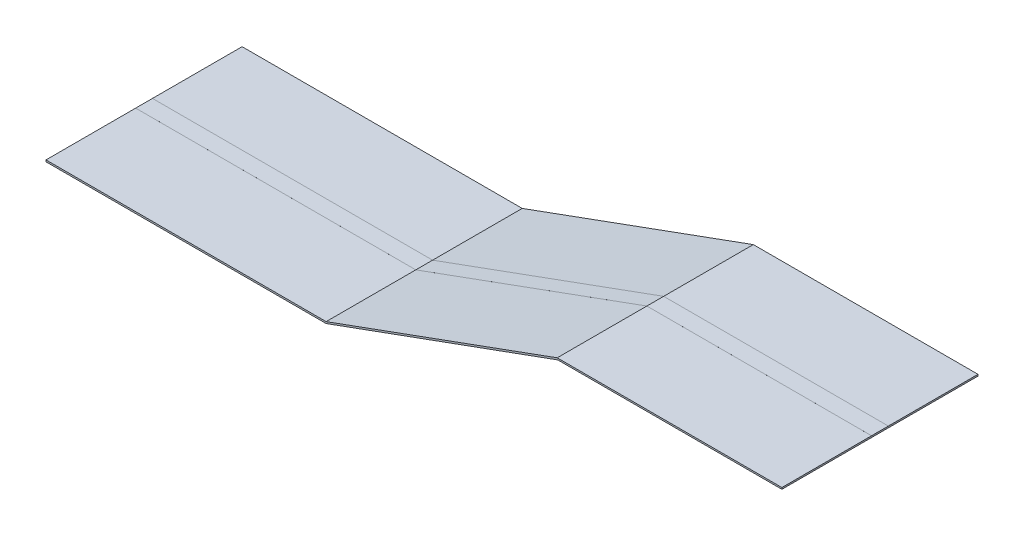
SolidWorks part; units mm, degrees
ref_plane "Front Plane" through (0, 0, 0) normal (0, 0, 1) x (1, 0, 0)
ref_plane "Top Plane" through (0, 0, 0) normal (0, 1, 0) x (1, 0, 0)
ref_plane "Right Plane" through (0, 0, 0) normal (1, 0, 0) x (0, 0, -1)
sketch "Sketch2" plane through (0, 0, 0) normal (0, 0, 1) x (1, 0, 0)
  line L0 (0, 0) -> (-500, 0)
  line L1 (-500, 0) -> (-500, 3)
  line L2 (-500, 3) -> (0, 3)
  line L3 (0, 3) -> (412.4375, 153.3075)
  line L5 (413.4648, 150.4889) -> (0, 0)
  line L6 (413.4648, 150.4889) -> (813.4648, 150.4889)
  line L7 (412.4375, 153.3075) -> (813.4648, 153.3075)
  line L8 (813.4648, 153.3075) -> (813.4648, 150.4889)
  dimension "D1" = 3
  dimension "D2" = 3
  dimension "D3" = 440
  dimension "D4" = 500
  dimension "D5" = 500
  dimension "D6" = 20
  dimension "D7" = 2.8187
  dimension "D8" = 160
  dimension "D9" = 400
  dimension "D10" = 438.9727
extrude "Boss-Extrude3" add sketch "Sketch2" along normal blind 350
sketch "Sketch5" plane through (0, 3, 0) normal (0, 1, 0) x (1, 0, 0)
  line L0 (0, -175) -> (-500, -175) construction
  line L1 (0, -350) -> (0, 0) construction
  line L2 (-500, -350) -> (-500, 0) construction
  line L4 (-500, -190) -> (0, -190)
  line L5 (-500, -190) -> (-500, -160)
  line L6 (-500, -160) -> (0, -160)
  line L7 (0, -190) -> (0, -160)
  line L8 (-500, -190) -> (0, -160) construction
  line L9 (-500, -160) -> (0, -190) construction
  point P6 (-250, -175)
  dimension "D1" = 15
extrude "Boss-Extrude4" add sketch "Sketch5" along normal blind 0.01
sketch "Sketch6" plane through (-0.9651, 2.6483, 0) normal (-0.3424, 0.9396, 0) x (0.9396, 0.3424, 0)
  line L0 (440, -175) -> (1.0272, -175) construction
  line L1 (440, -350) -> (440, 0) construction
  line L2 (1.0272, -190) -> (1.0272, -160) construction
  line L4 (440, -190) -> (1.0272, -190)
  line L5 (440, -190) -> (440, -160)
  line L6 (440, -160) -> (1.0272, -160)
  line L7 (1.0272, -190) -> (1.0272, -160)
  line L8 (440, -190) -> (1.0272, -160) construction
  line L9 (440, -160) -> (1.0272, -190) construction
  point P6 (220.5136, -175)
extrude "Boss-Extrude5" add sketch "Sketch6" along normal blind 0.01
sketch "Sketch7" plane through (0, 153.3075, 0) normal (0, 1, 0) x (1, 0, 0)
  line L0 (813.4648, -175) -> (412.4341, -175) construction
  line L1 (813.4648, -350) -> (813.4648, 0) construction
  line L2 (412.4341, -190) -> (412.4341, -160) construction
  line L4 (813.4613, -190) -> (412.4375, -190)
  line L5 (813.4613, -190) -> (813.4613, -160)
  line L6 (813.4613, -160) -> (412.4375, -160)
  line L7 (412.4375, -190) -> (412.4375, -160)
  line L8 (813.4613, -190) -> (412.4375, -160) construction
  line L9 (813.4613, -160) -> (412.4375, -190) construction
  point P6 (612.9494, -175)
extrude "Boss-Extrude6" add sketch "Sketch7" along normal blind 0.01
sketch "Sketch8" plane through (0, 3.01, 0) normal (0, 1, 0) x (1, 0, 0)
  line L0 (-500, -175) -> (-0.0018, -175) construction
  line L1 (-500, -160) -> (-500, -190) construction
  line L2 (-0.0018, -190) -> (-0.0018, -160) construction
